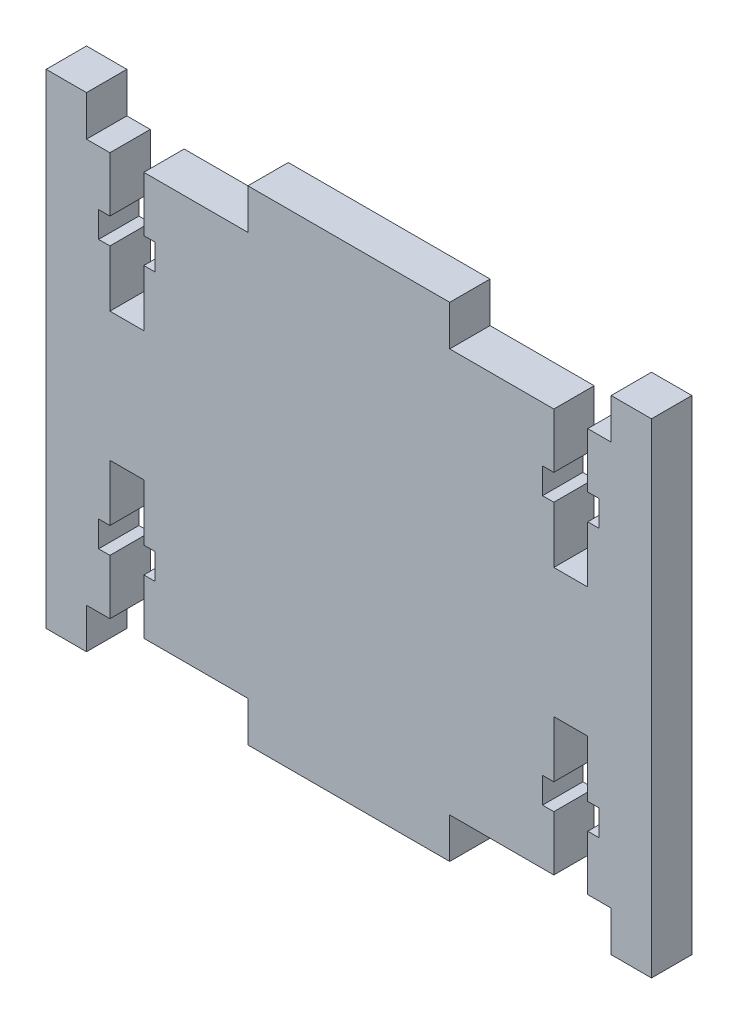
SolidWorks part; units mm, degrees
ref_plane "Front Plane" through (0, 0, 0) normal (0, 0, 1) x (1, 0, 0)
ref_plane "Top Plane" through (0, 0, 0) normal (0, 1, 0) x (1, 0, 0)
ref_plane "Right Plane" through (0, 0, 0) normal (1, 0, 0) x (0, 0, -1)
sketch "Sketch1" plane through (0, 0, 0) normal (0, 0, 1) x (1, 0, 0)
  line L0 (32.5, 55) -> (32.5, 28.1875) construction
  line L1 (0, 50) -> (65, 50)
  line L2 (0, 50) -> (0, 0)
  line L3 (0, 0) -> (65, 0)
  line L4 (65, 50) -> (65, 0)
  line L5 (20, 50) -> (45, 50)
  line L6 (20, 50) -> (20, 55)
  line L7 (20, 55) -> (45, 55)
  line L8 (45, 50) -> (45, 55)
  line L9 (2.9, 50) -> (7.1, 50)
  line L10 (2.9, 50) -> (2.9, 33)
  line L11 (2.9, 33) -> (7.1, 33)
  line L12 (7.1, 50) -> (7.1, 33)
  line L13 (1.5, 43.2) -> (8.5, 43.2)
  line L14 (1.5, 43.2) -> (1.5, 40)
  line L15 (1.5, 40) -> (8.5, 40)
  line L16 (8.5, 43.2) -> (8.5, 40)
  line L17 (63.5, 40) -> (56.5, 40)
  line L18 (56.5, 43.2) -> (56.5, 40)
  line L19 (63.5, 43.2) -> (56.5, 43.2)
  line L20 (63.5, 43.2) -> (63.5, 40)
  line L21 (62.1, 33) -> (57.9, 33)
  line L22 (57.9, 50) -> (57.9, 33)
  line L23 (62.1, 50) -> (57.9, 50)
  line L24 (62.1, 50) -> (62.1, 33)
  line L25 (0, 25) -> (24.3939, 25) construction
  line L26 (20, -5) -> (45, -5)
  line L27 (45, 0) -> (45, -5)
  line L28 (20, 0) -> (45, 0)
  line L29 (20, 0) -> (20, -5)
  line L30 (62.1, 0) -> (62.1, 17)
  line L31 (62.1, 0) -> (57.9, 0)
  line L32 (57.9, 0) -> (57.9, 17)
  line L33 (62.1, 17) -> (57.9, 17)
  line L34 (63.5, 6.8) -> (63.5, 10)
  line L35 (63.5, 6.8) -> (56.5, 6.8)
  line L36 (56.5, 6.8) -> (56.5, 10)
  line L37 (63.5, 10) -> (56.5, 10)
  line L38 (1.5, 10) -> (8.5, 10)
  line L39 (8.5, 6.8) -> (8.5, 10)
  line L40 (1.5, 6.8) -> (8.5, 6.8)
  line L41 (1.5, 6.8) -> (1.5, 10)
  line L42 (2.9, 17) -> (7.1, 17)
  line L43 (7.1, 0) -> (7.1, 17)
  line L44 (2.9, 0) -> (7.1, 0)
  line L45 (2.9, 0) -> (2.9, 17)
  line L46 (65, -5) -> (70, -5)
  line L47 (0, 55) -> (-5, 55)
  line L48 (0, 55) -> (0, -5)
  line L49 (0, -5) -> (-5, -5)
  line L50 (-5, 55) -> (-5, -5)
  line L51 (70, 55) -> (70, -5)
  line L52 (65, 55) -> (70, 55)
  line L53 (65, 55) -> (65, -5)
  point P17 (5, 43.2)
  point P18 (5, 33)
  dimension "D1" = 50
  dimension "D2" = 5
  dimension "D3" = 25
  dimension "D4" = 20
  dimension "D5" = 20
  dimension "D6" = 7
  dimension "D7" = 3.2
  dimension "D8" = 6.8
  dimension "D9" = 17
  dimension "D10" = 4.2
  dimension "D11" = 5
  dimension "D12" = 5
extrude "Boss-Extrude1" add sketch "Sketch1" along normal blind 5 contours L3 L45 L40 L41 L38 L42 L43 L39 L32 L35 L36 L37 L33 L30 L34 L4 L1 L24 L19 L20 L17 L21 L22 L18 L12 L13 L16 L15 L11 L10 | L1 L8 L7 L6 | L3 L29 L26 L27 | L48 L47 L50 L49 | L46 L51 L52 L53
